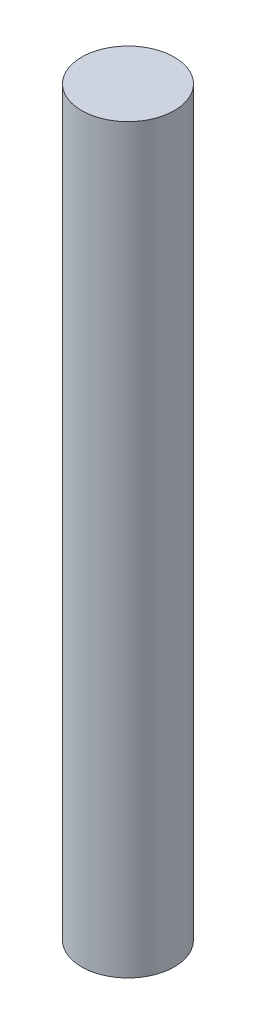
SolidWorks part; units mm, degrees
ref_plane "Front Plane" through (0, 0, 0) normal (0, 0, 1) x (1, 0, 0)
ref_plane "Top Plane" through (0, 0, 0) normal (0, 1, 0) x (1, 0, 0)
ref_plane "Right Plane" through (0, 0, 0) normal (1, 0, 0) x (0, 0, -1)
sketch "Sketch1" plane through (0, 0, 0) normal (0, 1, 0) x (1, 0, 0)
  circle A0 centre (0, 0) radius 1.5875
  dimension "D1" = 3.175
extrude "Boss-Extrude1" add sketch "Sketch1" along normal blind 25.4 contours A0
